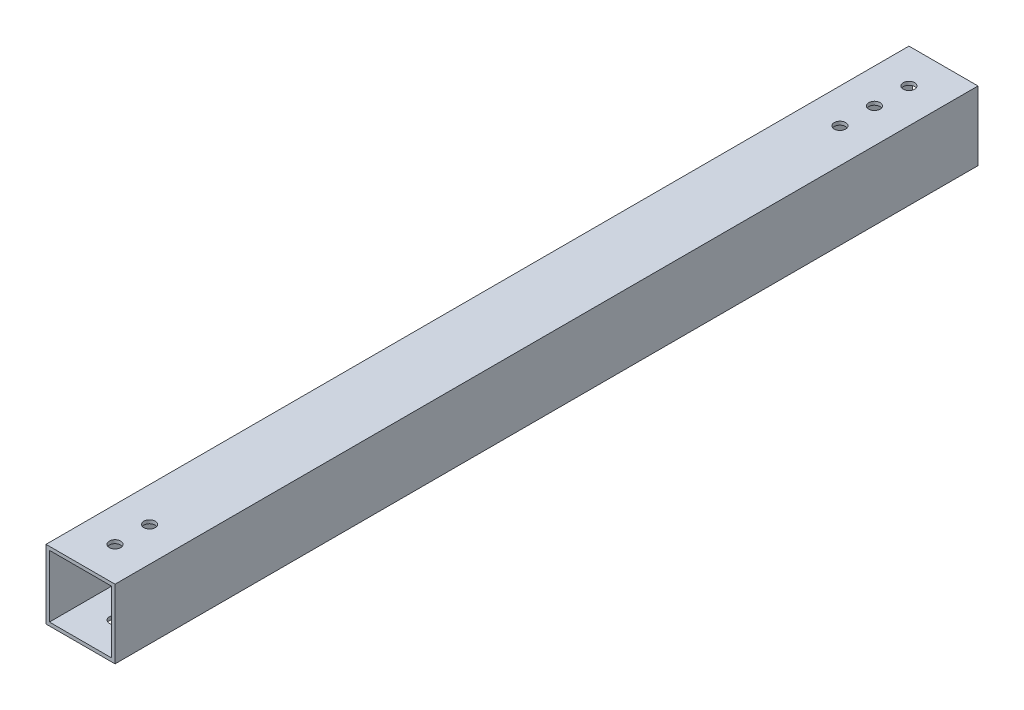
SolidWorks part; units mm, degrees
ref_plane "前视基准面" through (0, 0, 0) normal (0, 0, 1) x (1, 0, 0)
ref_plane "上视基准面" through (0, 0, 0) normal (0, 1, 0) x (1, 0, 0)
ref_plane "右视基准面" through (0, 0, 0) normal (1, 0, 0) x (0, 0, -1)
other "Configuration Table"
sketch "草图1" plane through (0, 0, 0) normal (0, 0, 1) x (1, 0, 0)
  line L1 (-9, 9) -> (9, 9)
  line L2 (-9, 9) -> (-9, -9)
  line L3 (-9, -9) -> (9, -9)
  line L4 (9, 9) -> (9, -9)
  line L5 (-9, 9) -> (9, -9) construction
  line L6 (-9, -9) -> (9, 9) construction
  line L7 (-10, 10) -> (10, 10)
  line L8 (-10, 10) -> (-10, -10)
  line L9 (-10, -10) -> (10, -10)
  line L10 (10, 10) -> (10, -10)
  line L11 (-10, 10) -> (10, -10) construction
  line L12 (-10, -10) -> (10, 10) construction
  point P0 (0, 0)
  point P6 (0, 0)
  dimension "D1" = 18
  dimension "D2" = 18
  dimension "D3" = 20
  dimension "D4" = 20
extrude "凸台-拉伸1" add sketch "草图1" along normal blind 250
sketch "草图2" plane through (0, 10, 0) normal (0, 1, 0) x (1, 0, 0)
  line L0 (0, 0) -> (0, -10) construction
  line L1 (0, -10) -> (0, -20) construction
  line L2 (10, -250) -> (10, 0) construction
  line L3 (10, -250) -> (-10, -250) construction
  circle A0 centre (0, -10) radius 1.65
  circle A1 centre (0, -20) radius 1.65
  circle A2 centre (0, -30) radius 1.65
  circle A3 centre (0, -240) radius 1.65
  circle A4 centre (0, -230) radius 1.65
  dimension "D3" = 3.3
  dimension "D4" = 3.3
  dimension "D5" = 3.3
  dimension "D8" = 3.3
  dimension "D9" = 3.3
  dimension "D1" = 10
  dimension "D2" = 10
  dimension "D6" = 10
  dimension "D7" = 10
  dimension "D10" = 10
  dimension "D11" = 10
extrude "切除-拉伸1" cut sketch "草图2" against normal through all
